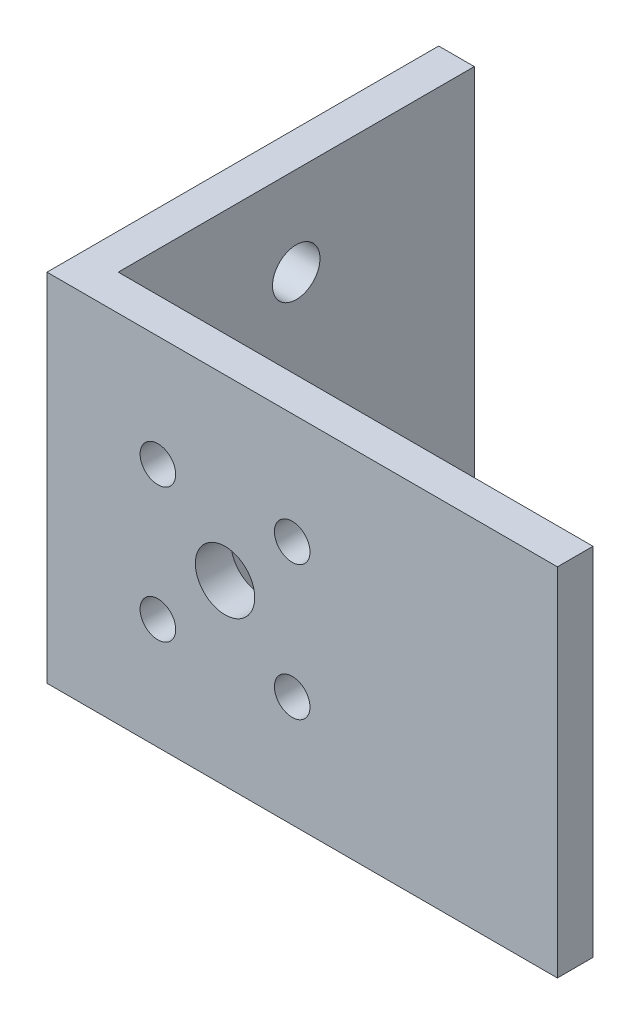
SolidWorks part; units mm, degrees
ref_plane "前视基准面" through (0, 0, 0) normal (0, 0, 1) x (1, 0, 0)
ref_plane "上视基准面" through (0, 0, 0) normal (0, 1, 0) x (1, 0, 0)
ref_plane "右视基准面" through (0, 0, 0) normal (1, 0, 0) x (0, 0, -1)
sketch "草图2" plane through (0, 0, 0) normal (0, 1, 0) x (1, 0, 0)
  line L0 (0, 0) -> (43, 0)
  line L1 (43, 0) -> (43, 3)
  line L2 (43, 3) -> (3, 3)
  line L3 (3, 3) -> (3, 33)
  line L4 (3, 33) -> (0, 33)
  line L5 (0, 33) -> (0, 0)
  dimension "D1" = 40
  dimension "D2" = 30
  dimension "D3" = 3
  dimension "D4" = 3
extrude "凸台-拉伸1" add sketch "草图2" along normal blind 30
sketch "草图4" plane through (0, 0, 0) normal (-1, 0, 0) x (0, 0, 1)
  line L0 (0, 30) -> (0, 0) construction
  line L1 (-33, 30) -> (0, 30) construction
  circle A0 centre (-18, 7.5) radius 2
  circle A1 centre (-18, 22.5) radius 2
  dimension "D2" = 7.5
  dimension "D3" = 4
  dimension "D1" = 18
  dimension "D4" = 15
extrude "切除-拉伸1" cut sketch "草图4" against normal up to next
sketch "草图5" plane through (0, 0, -3) normal (0, 0, -1) x (-1, 0, 0)
  line L0 (-43, 0) -> (-3, 0) construction
  line L1 (-3, 30) -> (-3, 0) construction
  line L2 (-43, 30) -> (-3, 30) construction
  circle A0 centre (-15, 15) radius 2.5
  circle A1 centre (-20.6569, 9.3431) radius 1.5
  circle A2 centre (-9.3431, 9.3431) radius 1.5
  circle A3 centre (-20.6569, 20.6569) radius 1.5
  circle A4 centre (-9.3431, 20.6569) radius 1.5
  dimension "D2" = 5
  dimension "D1" = 12
  dimension "D5" = 16
  dimension "D4" = 3
  dimension "D9" = 9.3431
  dimension "D10" = 3
  dimension "D11" = 3
  dimension "D12" = 3
  dimension "D3" = 15
  dimension "D6" = 8
  dimension "D7" = 16
  dimension "D8" = 8
  dimension "D13" = 9.3431
extrude "切除-拉伸2" cut sketch "草图5" against normal up to next
